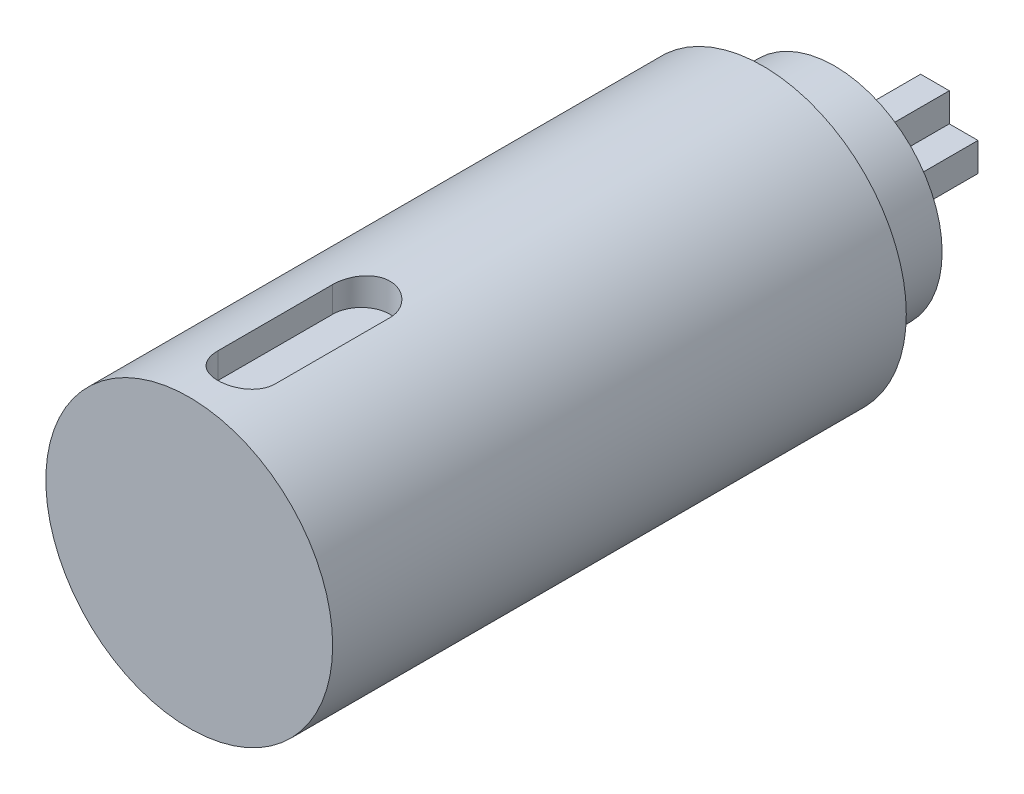
SolidWorks part; units mm, degrees
ref_plane "前视基准面" through (0, 0, 0) normal (0, 0, 1) x (1, 0, 0)
ref_plane "上视基准面" through (0, 0, 0) normal (0, 1, 0) x (1, 0, 0)
ref_plane "右视基准面" through (0, 0, 0) normal (1, 0, 0) x (0, 0, -1)
sketch "草图1" plane through (0, 0, 0) normal (0, 0, 1) x (1, 0, 0)
  circle A0 centre (0, 0) radius 7.5
  dimension "D1" = 15
extrude "凸台-拉伸1" add sketch "草图1" along normal blind 5
sketch "草图2" plane through (0, 0, 0) normal (0, 0, -1) x (-1, 0, 0)
  line L1 (-3, 1) -> (3, 1)
  line L2 (-3, 1) -> (-3, -1)
  line L3 (-3, -1) -> (3, -1)
  line L4 (3, 1) -> (3, -1)
  line L5 (0, -1) -> (0, 1) construction
  line L6 (-3, 0) -> (3, 0) construction
  line L7 (-1, 3) -> (1, 3)
  line L8 (-1, 3) -> (-1, -3)
  line L9 (-1, -3) -> (1, -3)
  line L10 (1, 3) -> (1, -3)
  line L11 (0, -3) -> (0, 3) construction
  line L12 (-1, 0) -> (1, 0) construction
  point P0 (0, 0)
  point P4 (0, 0)
  dimension "D1" = 6
  dimension "D2" = 6
  dimension "D3" = 2
  dimension "D4" = 2
extrude "凸台-拉伸2" add sketch "草图2" along normal blind 7 contours L8 L1 L2 L3 | L10 L7 L8 L1 | L1 L10 L3 L4 | L10 L1 L8 L3 | L10 L3 L8 L9
sketch "草图3" plane through (0, 0, 5) normal (0, 0, 1) x (1, 0, 0)
  circle A0 centre (0, 0) radius 10
  dimension "D1" = 20
extrude "凸台-拉伸3" add sketch "草图3" along normal blind 40
ref_plane "基准面1" through (0, 10, 0) normal (0, 1, 0) x (1, 0, 0)
sketch "草图4" plane through (0, 10, 0) normal (0, 1, 0) x (1, 0, 0)
  line L0 (0, -41) -> (0, -33) construction
  line L1 (-2, -41) -> (-2, -33)
  line L2 (2, -41) -> (2, -33)
  line L3 (-10, -45) -> (10, -45) construction
  arc A0 (-2, -41) -> (2, -41) centre (0, -41) ccw
  arc A1 (2, -33) -> (-2, -33) centre (0, -33) ccw
  point P3 (0, -37)
  point P10 (0, 0)
  dimension "D1" = 2
  dimension "D2" = 8
  dimension "D3" = 4
extrude "切除-拉伸1" cut sketch "草图4" against normal blind 2
